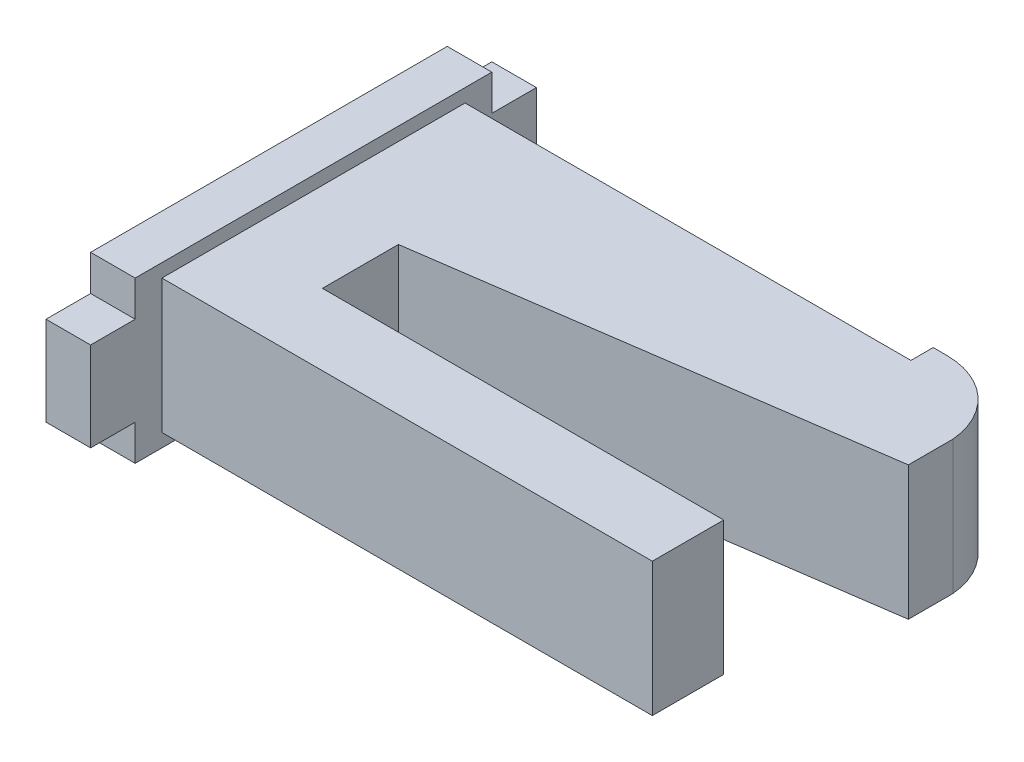
SolidWorks part; units mm, degrees
material "PLA"
ref_plane "Front Plane" through (0, 0, 0) normal (0, 0, 1) x (1, 0, 0)
ref_plane "Top Plane" through (0, 0, 0) normal (0, 1, 0) x (1, 0, 0)
ref_plane "Right Plane" through (0, 0, 0) normal (1, 0, 0) x (0, 0, -1)
sketch "Sketch2" plane through (0, 0, 0) normal (0, 1, 0) x (1, 0, 0)
  line L0 (0, 0) -> (0, 40)
  line L1 (0, 40) -> (5, 40)
  line L2 (5, 40) -> (5, 37)
  line L3 (5, 37) -> (55, 37)
  line L4 (55, 37) -> (55, 39.5)
  line L6 (65, 31.7118) -> (65, 26.7118)
  line L7 (65, 26.7118) -> (15, 19.5183)
  line L8 (15, 19.5183) -> (15, 3)
  line L9 (15, 3) -> (5, 3)
  line L10 (5, 3) -> (5, 0)
  line L11 (5, 0) -> (0, 0)
  line L12 (55, 39.5) -> (56.5, 39.5)
  arc A1 (56.5, 39.5) -> (65, 31.7118) centre (56.5, 30.9675) cw
  point P3 (2.5, 0)
  dimension "D1" = 5
  dimension "D2" = 3
  dimension "D3" = 2.5
  dimension "D4" = 50
  dimension "D5" = 50
  dimension "D6" = 10
  dimension "D7" = 5
  dimension "D8" = 5
  dimension "D9" = 40
  dimension "D10" = 3
  dimension "D11" = 1.5
  dimension "D12" = 10.2882
  dimension "D13" = 17.4817
extrude "Boss-Extrude1" add sketch "Sketch2" along normal blind 15
sketch "Sketch4" plane through (0, 15, 0) normal (0, 1, 0) x (1, 0, 0)
  line L0 (5, 40) -> (5, 0)
  line L1 (5, 0) -> (0, 0)
  line L2 (0, 0) -> (0, 40)
  line L3 (0, 40) -> (5, 40)
extrude "Boss-Extrude2" add sketch "Sketch4" along normal blind 1.5
sketch "Sketch5" plane through (0, 0, 0) normal (0, -1, 0) x (1, 0, 0)
  line L0 (0, 0) -> (5, 0)
  line L1 (5, 0) -> (5, -40)
  line L2 (5, -40) -> (0, -40) construction
  line L3 (5, -37) -> (5, -40) construction
  line L4 (5, -40) -> (0, -40)
  line L5 (0, -40) -> (0, 0)
extrude "Boss-Extrude3" add sketch "Sketch5" along normal blind 1.5
sketch "Sketch6" plane through (15, 0, 0) normal (1, 0, 0) x (0, 0, -1)
  line L0 (3, 15) -> (11, 15)
  line L1 (3, 15) -> (37, 15) construction
  line L2 (11, 15) -> (11, 0)
  line L3 (37, 0) -> (3, 0) construction
  line L4 (11, 0) -> (3, 0)
  line L5 (3, 0) -> (3, 15)
  dimension "D1" = 8
extrude "Boss-Extrude4" add sketch "Sketch6" along normal blind 45 contours L5 L0 L2 L4
sketch "Sketch7" plane through (0, 0, 0) normal (0, 0, 1) x (1, 0, 0)
  line L0 (0, 12.5) -> (5, 12.5)
  line L1 (0, 16.5) -> (0, -1.5) construction
  line L2 (5, 15) -> (5, 0) construction
  line L3 (5, 12.5) -> (5, 2.5)
  line L4 (5, 2.5) -> (0, 2.5)
  line L5 (0, 2.5) -> (0, 12.5)
  line L6 (0, 16.5) -> (5, 16.5) construction
  line L8 (5, -1.5) -> (0, -1.5) construction
  dimension "D1" = 4
  dimension "D2" = 4
extrude "Boss-Extrude5" add sketch "Sketch7" along normal blind 5 contours L5 L0 L3 L4
sketch "Sketch8" plane through (0, 0, -40) normal (0, 0, -1) x (-1, 0, 0)
  line L0 (-5, 12.5) -> (0, 12.5)
  line L1 (-5, 16.5) -> (-5, -1.5) construction
  line L2 (0, 16.5) -> (0, -1.5) construction
  line L3 (0, 12.5) -> (0, 2.5)
  line L4 (0, 2.5) -> (-5, 2.5)
  line L5 (-5, 2.5) -> (-5, 12.5)
  line L6 (-5, 16.5) -> (0, 16.5) construction
  line L7 (0, -1.5) -> (-5, -1.5) construction
  dimension "D1" = 4
  dimension "D2" = 4
extrude "Boss-Extrude6" add sketch "Sketch8" along normal blind 5 contours L5 L0 L3 L4
